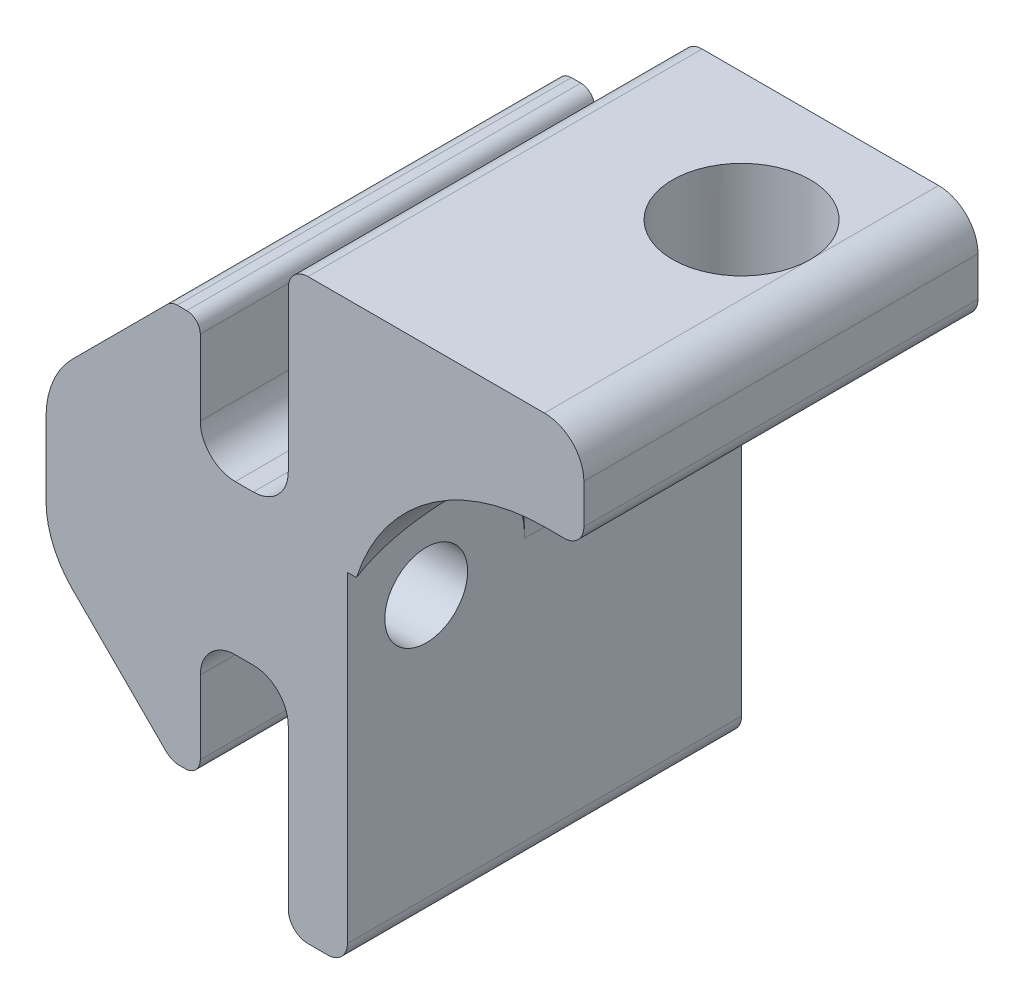
SolidWorks part; units mm, degrees
ref_plane "Front Plane" through (0, 0, 0) normal (0, 0, 1) x (1, 0, 0)
ref_plane "Top Plane" through (0, 0, 0) normal (0, 1, 0) x (1, 0, 0)
ref_plane "Right Plane" through (0, 0, 0) normal (1, 0, 0) x (0, 0, -1)
sketch "Sketch1" plane through (0, 0, 0) normal (0, 0, 1) x (1, 0, 0)
  line L0 (38.3, 9.8814) -> (38.3, 10.7456)
  line L1 (38.3, 27.3535) -> (38.3, 28.2156)
  line L2 (39.3, 33.711) -> (41.3, 33.711)
  line L3 (33.836, 28.448) -> (33.836, 24.6302)
  line L5 (51.3, 28.711) -> (52.3, 28.711)
  line L6 (53.3, 29.711) -> (53.3, 31.711)
  line L7 (51.3, 33.711) -> (41.3, 33.711)
  line L8 (41.3, 18.711) -> (41.3, 5.3943)
  line L9 (40.3, 4.3943) -> (39.3, 4.3943)
  line L327 (33.836, 28.448) -> (33.836, 24.6302)
  line L328 (35.6108, 22.8554) -> (36.5252, 22.8554)
  line L329 (38.3, 24.6302) -> (38.3, 27.3535)
  line L330 (38.3, 28.2156) -> (38.3, 32.711)
  line L426 (38.3, 5.3943) -> (38.3, 9.8814)
  line L427 (38.3, 10.7456) -> (38.3, 13.4698)
  line L428 (36.5252, 15.2446) -> (35.6108, 15.2446)
  line L429 (33.836, 13.4698) -> (33.836, 9.7387)
  line L430 (33.0603, 8.963) -> (32.7869, 8.963)
  line L431 (32.0904, 9.2515) -> (27.339, 14.0029)
  line L432 (26.0064, 17.2201) -> (26.0064, 20.8799)
  line L433 (27.339, 24.0971) -> (32.1771, 28.9352)
  line L434 (32.6643, 29.137) -> (33.147, 29.137)
  arc A0 (41.3, 18.711) -> (51.3, 28.711) centre (51.3, 18.711) cw
  arc A1 (53.3, 31.711) -> (51.3, 33.711) centre (51.3, 31.711) ccw
  arc A2 (39.3, 33.711) -> (38.3, 32.711) centre (39.3, 32.711) ccw
  arc A3 (39.3, 4.3943) -> (38.3, 5.3943) centre (39.3, 5.3943) cw
  arc A4 (40.3, 4.3943) -> (41.3, 5.3943) centre (40.3, 5.3943) ccw
  arc A5 (52.3, 28.711) -> (53.3, 29.711) centre (52.3, 29.711) ccw
  arc A360 (33.836, 28.448) -> (33.147, 29.137) centre (33.147, 28.448) ccw
  arc A361 (33.836, 24.6302) -> (35.6108, 22.8554) centre (35.6108, 24.6302) ccw
  arc A362 (36.5252, 22.8554) -> (38.3, 24.6302) centre (36.5252, 24.6302) ccw
  arc A473 (38.3, 13.4698) -> (36.5252, 15.2446) centre (36.5252, 13.4698) ccw
  arc A474 (35.6108, 15.2446) -> (33.836, 13.4698) centre (35.6108, 13.4698) ccw
  arc A475 (33.0603, 8.963) -> (33.836, 9.7387) centre (33.0603, 9.7387) ccw
  arc A476 (32.0904, 9.2515) -> (32.7869, 8.963) centre (32.7869, 9.9481) ccw
  arc A477 (26.0064, 17.2201) -> (27.339, 14.0029) centre (30.5562, 17.2201) ccw
  arc A478 (27.339, 24.0971) -> (26.0064, 20.8799) centre (30.5562, 20.8799) ccw
  arc A479 (32.6643, 29.137) -> (32.1771, 28.9352) centre (32.6643, 28.448) ccw
  dimension "D1" = 10
  dimension "D2" = 2
  dimension "D3" = 1
  dimension "D4" = 1
extrude "Boss-Extrude1" add sketch "Sketch1" against normal blind 20 contours L434 A479 L433 A478 L432 A477 L431 A476 L430 A475 L429 A474 L428 A473 L427 L0 L426 L9 L8 A0 L5 L6 L7 L2 L330 L1 L329 A362 L328 A361 L3 A360
sketch "Sketch2" plane through (0, 33.711, 0) normal (0, 1, 0) x (1, 0, 0)
  circle A0 centre (47.8, 13.5) radius 3.5
extrude "Cut-Extrude1" cut sketch "Sketch2" against normal through all
sketch "Sketch3" plane through (41.3, 0, 0) normal (1, 0, 0) x (0, 0, -1)
  circle A0 centre (4, 18.711) radius 2.1
extrude "Cut-Extrude2" cut sketch "Sketch3" against normal through all
sketch "Sketch4" plane through (41.3, 0, 0) normal (-1, 0, 0) x (0, 0, 1)
  line L0 (-6.1, 18.711) -> (-1.9, 18.711) construction
  circle A0 centre (-4, 18.711) radius 5
extrude "Cut-Extrude3" cut sketch "Sketch4" against normal blind 20
